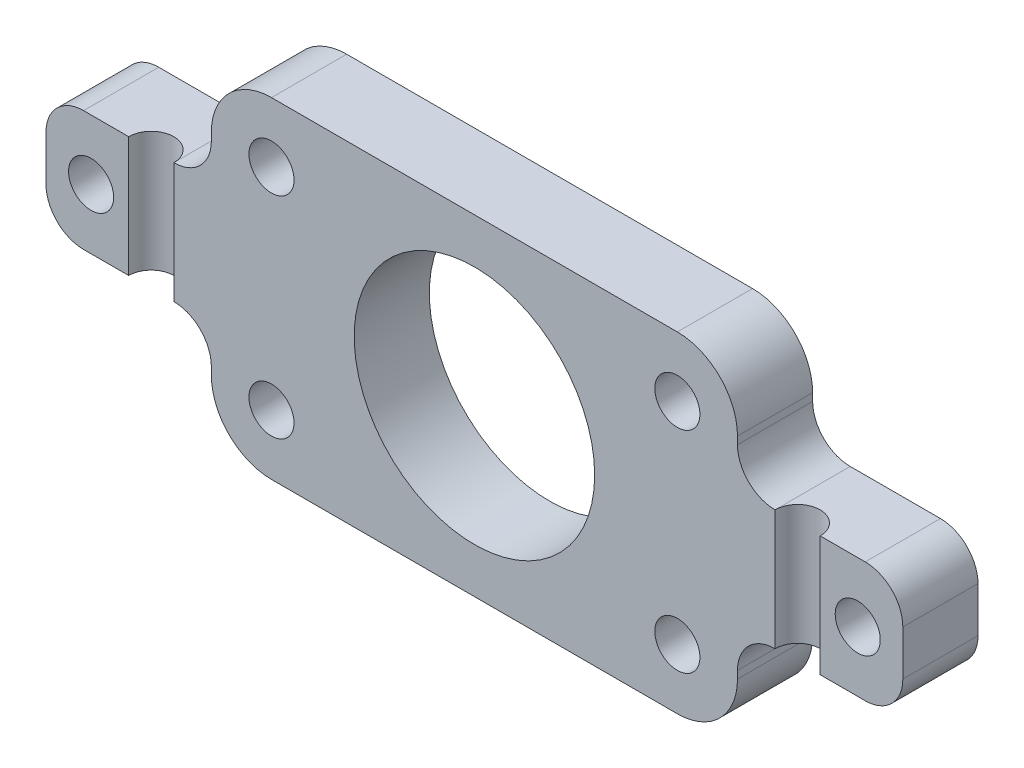
SolidWorks part; units mm, degrees
material "POM 乙缩醛共聚物"
ref_plane "前视基准面" through (0, 0, 0) normal (0, 0, 1) x (1, 0, 0)
ref_plane "上视基准面" through (0, 0, 0) normal (0, 1, 0) x (1, 0, 0)
ref_plane "右视基准面" through (0, 0, 0) normal (1, 0, 0) x (0, 0, -1)
sketch "草图1" plane through (0, 0, 0) normal (0, 0, 1) x (1, 0, 0)
  line L0 (0, 11) -> (57, 11) construction
  line L1 (0, 0) -> (57, 0) construction
  line L2 (0, 0) -> (0, 22) construction
  line L3 (0, 22) -> (57, 22) construction
  line L4 (57, 0) -> (57, 22) construction
  line L5 (2.5, 15) -> (8.5, 15)
  line L6 (11, 17.5) -> (11, 18)
  line L7 (28.5, 22) -> (28.5, 0) construction
  line L8 (11, 4.5) -> (11, 4)
  line L9 (2.5, 7) -> (8.5, 7)
  line L10 (46, 4.5) -> (46, 4)
  line L11 (54.5, 7) -> (48.5, 7)
  line L12 (46, 17.5) -> (46, 18)
  line L13 (54.5, 15) -> (48.5, 15)
  line L14 (0, 12.5) -> (0, 9.5)
  line L15 (15, 0) -> (42, 0)
  line L16 (57, 9.5) -> (57, 12.5)
  line L17 (42, 22) -> (15, 22)
  circle A0 centre (28.5, 11) radius 8
  arc A1 (11, 4) -> (15, 0) centre (15, 4) ccw
  arc A2 (46, 4) -> (42, 0) centre (42, 4) cw
  arc A3 (46, 18) -> (42, 22) centre (42, 18) ccw
  arc A4 (11, 18) -> (15, 22) centre (15, 18) cw
  arc A5 (54.5, 7) -> (57, 9.5) centre (54.5, 9.5) ccw
  arc A6 (54.5, 15) -> (57, 12.5) centre (54.5, 12.5) cw
  arc A7 (2.5, 7) -> (0, 9.5) centre (2.5, 9.5) cw
  arc A8 (2.5, 15) -> (0, 12.5) centre (2.5, 12.5) ccw
  arc A9 (11, 4.5) -> (8.5, 7) centre (8.5, 4.5) ccw
  arc A10 (46, 4.5) -> (48.5, 7) centre (48.5, 4.5) cw
  arc A11 (46, 17.5) -> (48.5, 15) centre (48.5, 17.5) ccw
  arc A12 (8.5, 15) -> (11, 17.5) centre (8.5, 17.5) ccw
  circle A13 centre (15, 18) radius 1.5
  circle A14 centre (15, 4) radius 1.5
  circle A15 centre (42, 18) radius 1.5
  circle A16 centre (42, 4) radius 1.5
  circle A17 centre (3, 11) radius 1.5
  circle A18 centre (28.5, 11) radius 8.5 construction
  circle A19 centre (15, 18) radius 3 construction
  circle A20 centre (3, 11) radius 3 construction
  circle A21 centre (54, 11) radius 1.5
  point P25 (11, 0)
  point P28 (46, 0)
  point P31 (46, 22)
  point P34 (11, 22)
  point P37 (57, 7)
  point P40 (57, 15)
  point P43 (0, 7)
  point P46 (0, 15)
  point P49 (11, 7)
  point P52 (46, 7)
  point P55 (46, 15)
  point P58 (11, 15)
  dimension "D3" = 16
  dimension "D4" = 4
  dimension "D6" = 4
  dimension "D7" = 2.5
  dimension "D8" = 3
  dimension "D9" = 3
  dimension "D10" = 3
  dimension "D11" = 17
  dimension "D12" = 6
  dimension "D13" = 6
  dimension "D1" = 22
  dimension "D2" = 57
  dimension "D5" = 11
extrude "凸台-拉伸1" add sketch "草图1" along normal blind 5
sketch "草图2" plane through (0, 15, 0) normal (0, 1, 0) x (1, 0, 0)
  line L0 (8.5, -5) -> (2.5, -5) construction
  line L1 (28.5, 0) -> (28.5, -5) construction
  line L2 (42, 0) -> (15, 0) construction
  line L3 (42, -5) -> (15, -5) construction
  circle A0 centre (7, -5) radius 1.5
  circle A1 centre (50, -5) radius 1.5
  dimension "D1" = 3
  dimension "D2" = 7
extrude "切除-拉伸1" cut sketch "草图2" against normal blind 11.5
